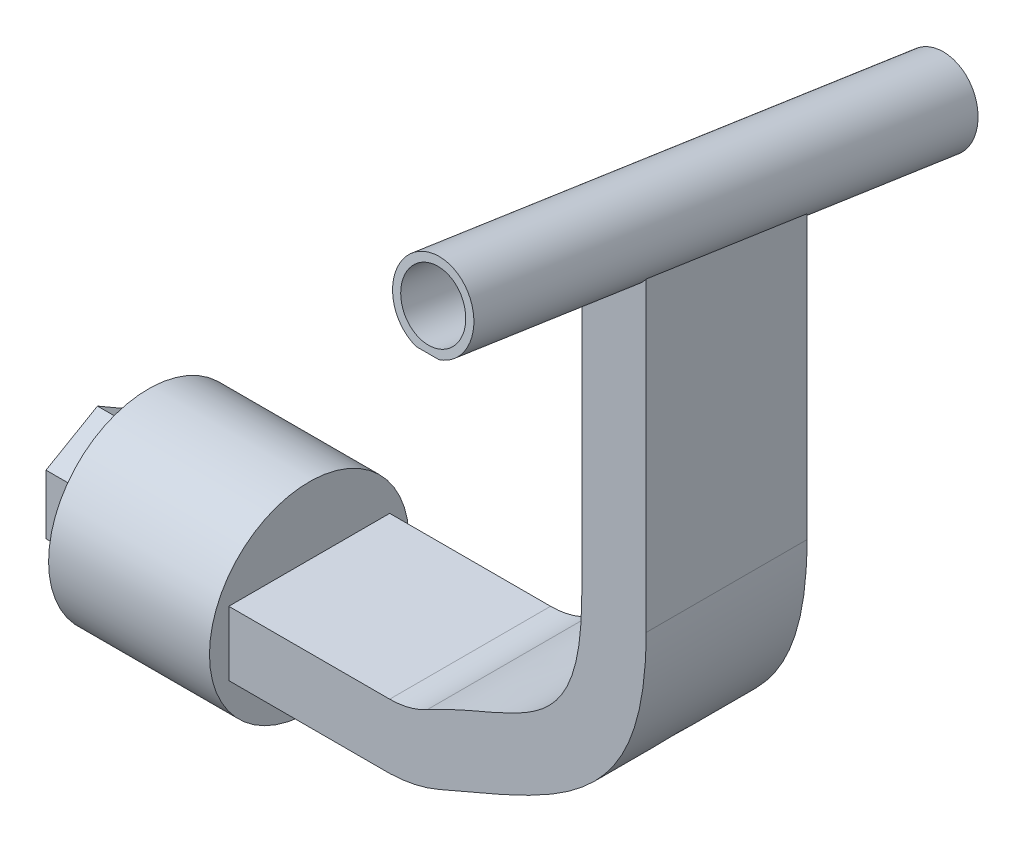
SolidWorks part; units mm, degrees
ref_plane "Front Plane" through (0, 0, 0) normal (0, 0, 1) x (1, 0, 0)
ref_plane "Top Plane" through (0, 0, 0) normal (0, 1, 0) x (1, 0, 0)
ref_plane "Right Plane" through (0, 0, 0) normal (1, 0, 0) x (0, 0, -1)
sketch "Sketch1" plane through (0, 0, 0) normal (0, 0, 1) x (1, 0, 0)
  line L0 (0, 0) -> (127, 0)
  line L1 (0, 0) -> (0, 50.8)
  line L2 (0, 50.8) -> (127, 50.8)
  line L3 (278.6095, 197.5817) -> (278.6095, 431.8)
  line L4 (278.6095, 431.8) -> (329.4095, 431.8)
  line L5 (329.4095, 431.8) -> (329.4095, 197.5817)
  arc A0 (127, 50.8) -> (156.6307, 58.4289) centre (127, 112.1574) ccw
  arc A1 (165.7638, 8.4566) -> (127, 0) centre (124.2989, 105.4533) cw
  spline S0 degree 3 poles (156.6307, 58.4289) (189.028, 76.2956) (253.7659, 94.019) (278.6095, 141.9699) (278.6095, 197.5817) knots 0 0 0 0 0.47511 1 1 1 1
  spline S1 degree 3 poles (165.7638, 8.4566) (215.9508, 29.9109) (293.75, 60.0248) (329.4095, 131.4091) (329.4095, 197.5817) knots 0 0 0 0 0.489737 1 1 1 1
  dimension "D3" = 50.8
  dimension "D1" = 127
  dimension "D2" = 50.8
  dimension "D4" = 50.8
  dimension "D5" = 50.8
  dimension "D6" = 50.8
  dimension "D7" = 381
extrude "Boss-Extrude1" add sketch "Sketch1" along normal blind 127
sketch "Sketch2" plane through (0, 0, 0) normal (-1, 0, 0) x (0, 0, 1)
  circle A0 centre (63.5, 25.4) radius 78.74
  dimension "D1" = 157.48
extrude "Boss-Extrude2" add sketch "Sketch2" along normal blind 127
sketch "Sketch3" plane through (-127, 0, 0) normal (-1, 0, 0) x (0, 0, 1)
  line L1 (63.5, 72.327) -> (22.86, 48.8635)
  line L2 (22.86, 48.8635) -> (22.86, 1.9365)
  line L3 (22.86, 1.9365) -> (63.5, -21.527)
  line L4 (63.5, -21.527) -> (104.14, 1.9365)
  line L5 (104.14, 1.9365) -> (104.14, 48.8635)
  line L6 (104.14, 48.8635) -> (63.5, 72.327)
  circle A0 centre (63.5, 25.4) radius 40.64 construction
  dimension "D1" = 81.28
extrude "Boss-Extrude3" add sketch "Sketch3" along normal blind 40.132
sketch "Sketch4" plane through (278.6095, 0, 0) normal (-1, 0, 0) x (0, 0, 1)
  line L2 (-123.9796, 390.1654) -> (273.9962, 449.2797)
  line L5 (-123.9796, 390.1654) -> (-135.0748, 464.8619)
  line L7 (273.9962, 449.2797) -> (262.901, 523.9761)
  line L9 (-135.0748, 464.8619) -> (262.901, 523.9761)
extrude "Boss-Extrude4" add sketch "Sketch4" against normal blind 63.5 and the other way blind 12.7
sketch "Sketch6" plane through (0, -9.5955, -64.6002) normal (0, -0.1469, -0.9891) x (-1, 0, 0)
  line L4 (-329.4095, 404.1469) -> (-278.6095, 404.1469) construction
  line L14 (-264.6395, 480.9329) -> (-343.3795, 480.9329)
  line L15 (-343.3795, 480.9329) -> (-343.3795, 402.8769)
  line L16 (-343.3795, 402.8769) -> (-264.6395, 402.8769)
  line L17 (-264.6395, 402.8769) -> (-264.6395, 480.9329)
  line L18 (-264.6395, 480.9329) -> (-343.3795, 480.9329)
  line L19 (-343.3795, 480.9329) -> (-343.3795, 402.8769)
  line L20 (-343.3795, 402.8769) -> (-264.6395, 402.8769)
  line L21 (-264.6395, 402.8769) -> (-264.6395, 480.9329)
  circle A0 centre (-303.8835, 434.6269) radius 31.75
  line M6 (-265.9095, 479.6629) -> (-342.1095, 479.6629)
  line M7 (-342.1095, 479.6629) -> (-342.1095, 404.1469)
  line M8 (-342.1095, 404.1469) -> (-265.9095, 404.1469)
  line M9 (-265.9095, 404.1469) -> (-265.9095, 479.6629)
  dimension "D1" = 30.48
  dimension "D2" = 1.27
extrude "Cut-Extrude4" cut sketch "Sketch6" against normal through all contours A0 M8 M9 M6 M7
sketch "Sketch7" plane through (0, -9.5955, -64.6002) normal (0, -0.1469, -0.9891) x (-1, 0, 0)
  circle A0 centre (-303.8835, 434.6269) radius 25.4
  dimension "D1" = 50.8
extrude "Cut-Extrude5" cut sketch "Sketch7" against normal blind 304.8
sketch "Sketch8" plane through (278.6095, 0, 0) normal (-1, 0, 0) x (0, 0, 1)
  line L0 (0, 400.8774) -> (0, 426.2774)
  line L1 (0, 408.581) -> (0, 197.5817) construction
  line L2 (0, 408.581) -> (127, 427.4452) construction
  line L3 (127, 419.7416) -> (127, 445.1416)
  line L4 (127, 427.4452) -> (127, 197.5817) construction
  line L5 (127, 427.4452) -> (0, 408.581) construction
  line L6 (0, 426.2774) -> (127, 445.1416)
  line L7 (0, 400.8774) -> (127, 419.7416)
  dimension "D1" = 7.62
  dimension "D2" = 25.4
  dimension "D3" = 25.4
  dimension "D4" = 7.62
extrude "Boss-Extrude5" add sketch "Sketch8" against normal blind 50.8
sketch "Sketch9" plane through (0, -9.5955, -64.6002) normal (0, -0.1469, -0.9891) x (-1, 0, 0)
  circle A0 centre (-303.8835, 434.6269) radius 25.4
extrude "Cut-Extrude6" cut sketch "Sketch9" against normal through all
sketch "Sketch10" plane through (0, -9.5955, -64.6002) normal (0, -0.1469, -0.9891) x (-1, 0, 0)
  circle A0 centre (-303.8835, 434.6269) radius 28.4269
extrude "Boss-Extrude6" add sketch "Sketch10" against normal blind 152.4
